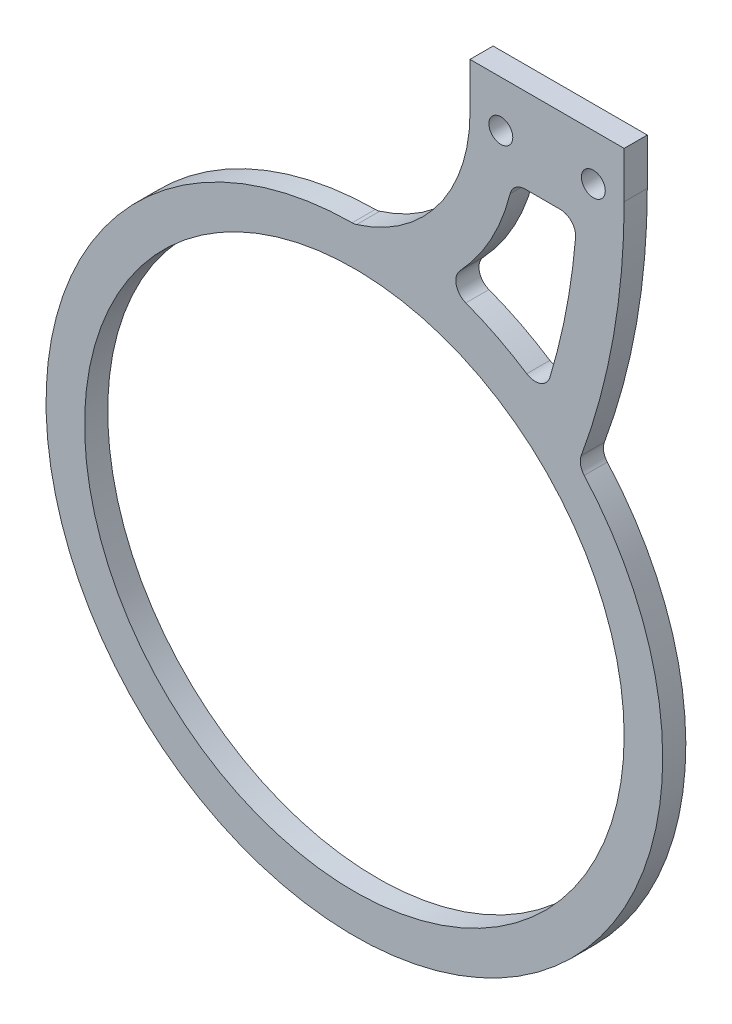
SolidWorks part; units mm, degrees
material "Thornel Mat VMA"
ref_plane "前视基准面" through (0, 0, 0) normal (0, 0, 1) x (1, 0, 0)
ref_plane "上视基准面" through (0, 0, 0) normal (0, 1, 0) x (1, 0, 0)
ref_plane "右视基准面" through (0, 0, 0) normal (1, 0, 0) x (0, 0, -1)
sketch "草图1" plane through (0, 0, 0) normal (0, 0, 1) x (1, 0, 0)
  line L0 (-4, 0) -> (-4, 6)
  line L1 (-4, 6) -> (16, 6)
  line L2 (16, 6) -> (16, 0)
  line L3 (6, 6) -> (6, -8.0386) construction
  line L4 (1.53, -5) -> (9.8524, -5)
  circle A0 centre (0, 0) radius 1.55
  circle A1 centre (12, 0) radius 1.55
  circle A2 centre (-19, -60) radius 35
  arc A3 (-19, -20) -> (10, -32.45) centre (-19, -60) ccw
  arc A4 (-19, -20) -> (-4, 0) centre (-24.8333, 0) ccw
  arc A5 (10, -32.45) -> (16, 0) centre (-74.7505, 0) ccw
  arc A6 (-7.6434, -20.6042) -> (1.53, -5) centre (-24.8333, 0) ccw
  arc A7 (5.5335, -27.1502) -> (9.8524, -5) centre (-74.7505, 0) ccw
  arc A8 (5.5335, -27.1502) -> (-7.6434, -20.6042) centre (-19, -60) ccw
  dimension "D2" = 3.1
  dimension "D3" = 60
  dimension "D8" = 70
  dimension "D9" = 5
  dimension "D11" = 6
  dimension "D12" = 6
  dimension "D13" = 6
  dimension "D1" = 12
  dimension "D4" = 6
  dimension "D5" = 4
  dimension "D6" = 4
  dimension "D7" = 25
  dimension "D10" = 4
  dimension "D14" = 5
extrude "凸台-拉伸1" add sketch "草图1" along normal blind 3
fillet "圆角1" radius 2 6 edges at (-7.6434, -20.6042, 1.5) (5.5335, -27.1502, 1.5) (9.8524, -5, 1.5) (1.53, -5, 1.5) (-19, -20, 1.5) (10, -32.45, 1.5)
